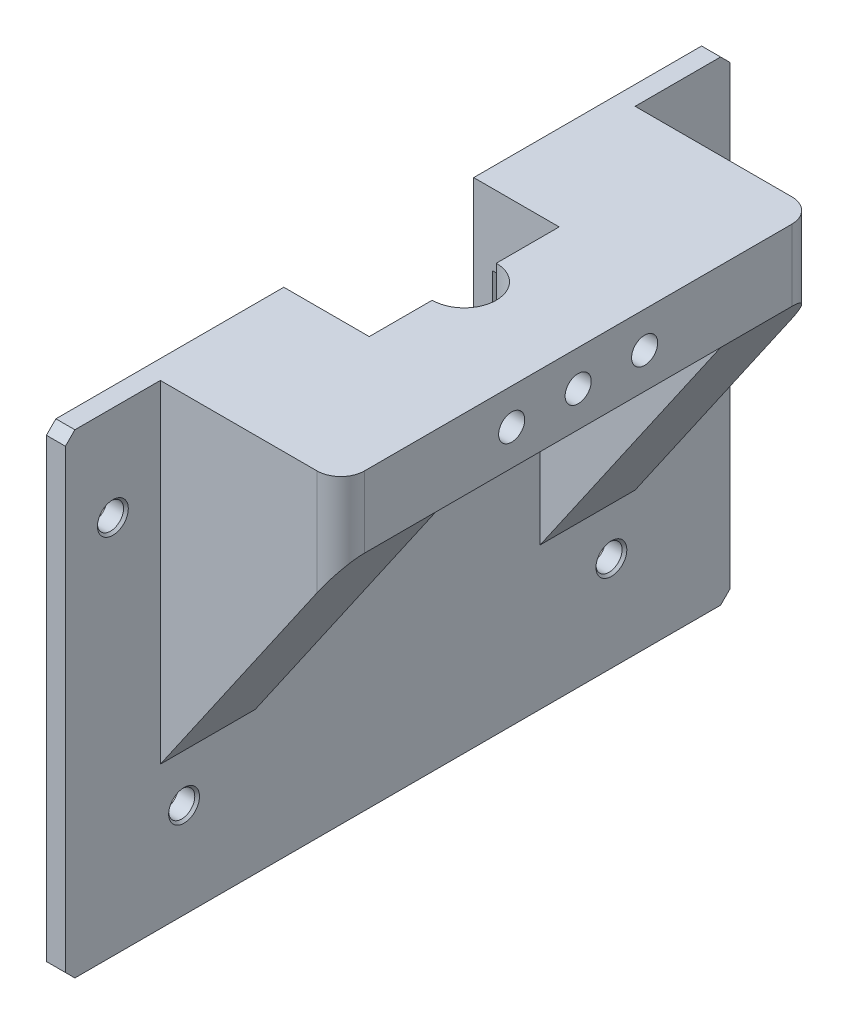
SolidWorks part; units mm, degrees
ref_plane "前视基准面" through (0, 0, 0) normal (0, 0, 1) x (1, 0, 0)
ref_plane "上视基准面" through (0, 0, 0) normal (0, 1, 0) x (1, 0, 0)
ref_plane "右视基准面" through (0, 0, 0) normal (1, 0, 0) x (0, 0, -1)
sketch "草图1" plane through (0, 0, 0) normal (1, 0, 0) x (0, 0, -1)
  line L1 (-70, 40) -> (70, 40)
  line L2 (-70, 40) -> (-70, -60)
  line L3 (-70, -60) -> (70, -60)
  line L4 (70, 40) -> (70, -60)
  dimension "D1" = 100
  dimension "D2" = 140
  dimension "D3" = 70
  dimension "D4" = 40
extrude "凸台-拉伸1" add sketch "草图1" along normal blind 4
sketch "草图9" plane through (4, 0, 0) normal (1, 0, 0) x (0, 0, -1)
  line L0 (70, -60) -> (70, 40) construction
  line L1 (-60, 20) -> (60, 20) construction
  line L2 (-60, 20) -> (-60, -40) construction
  line L3 (-60, -40) -> (60, -40) construction
  line L4 (60, 20) -> (60, -40) construction
  line L5 (70, 40) -> (-70, 40) construction
  circle A0 centre (-60, 20) radius 2.75
  circle A2 centre (60, 20) radius 2.75
  circle A4 centre (-45, -40) radius 2.75
  circle A5 centre (45, -40) radius 2.75
  dimension "D5" = 5.5
  dimension "D6" = 5.5
  dimension "D7" = 45
  dimension "D1" = 60
  dimension "D2" = 120
  dimension "D3" = 10
  dimension "D4" = 20
  dimension "D8" = 45
extrude "切除-拉伸3" cut sketch "草图9" against normal blind 8
chamfer "倒角2" distance 2 angle 45 4 edges at (2, -60, -70) (2, 40, -70) (2, 40, 70) (2, -60, 70)
sketch "草图11" plane through (4, 0, 0) normal (1, 0, 0) x (0, 0, -1)
  line L0 (68, 40) -> (-68, 40) construction
  line L1 (-20, 40) -> (20, 40)
  line L2 (-20, 40) -> (-20, -10)
  line L3 (-20, -10) -> (20, -10)
  line L4 (20, 40) -> (20, -10)
  dimension "D1" = 20
  dimension "D2" = 20
  dimension "D3" = 10
extrude "切除-拉伸5" cut sketch "草图11" against normal blind 5
sketch "草图12" plane through (4, 0, 0) normal (1, 0, 0) x (0, 0, -1)
  line L1 (-20, 40) -> (-30, 40)
  line L2 (-20, 40) -> (-20, 25)
  line L3 (-20, 25) -> (-30, 25)
  line L4 (-30, 40) -> (-30, 25)
  line L5 (20, 40) -> (30, 40)
  line L6 (20, 40) -> (20, 25)
  line L7 (20, 25) -> (30, 25)
  line L8 (30, 40) -> (30, 25)
  dimension "D1" = 10
  dimension "D2" = 10
  dimension "D3" = 15
  dimension "D4" = 15
extrude "凸台-拉伸2" add sketch "草图12" along normal blind 14
sketch "草图13" plane through (18, 0, 0) normal (1, 0, 0) x (0, 0, -1)
  line L1 (-30, 40) -> (30, 40)
  line L2 (-30, 40) -> (-30, 25)
  line L3 (-30, 25) -> (30, 25)
  line L4 (30, 40) -> (30, 25)
extrude "凸台-拉伸3" add sketch "草图13" along normal blind 14
sketch "草图14" plane through (0, 0, 30) normal (0, 0, 1) x (1, 0, 0)
  line L0 (4, 40) -> (4, -30)
  line L1 (4, 38) -> (4, -58) construction
  line L2 (4, -30) -> (32, 25)
  line L3 (32, 25) -> (32, 40)
  line L4 (32, 40) -> (4, 40)
  dimension "D1" = 55
extrude "凸台-拉伸4" add sketch "草图14" along normal blind 20
sketch "草图15" plane through (0, 0, -30) normal (0, 0, -1) x (-1, 0, 0)
  line L4 (-4, 40) -> (-32, 40)
  line L5 (-4, -30) -> (-4, 40)
  line L6 (-32, 25) -> (-4, -30)
  line L7 (-32, 40) -> (-32, 25)
  line L8 (-4, 40) -> (-32, 40)
  line L9 (-4, -30) -> (-4, 40)
  line L10 (-32, 25) -> (-4, -30)
  line L11 (-32, 40) -> (-32, 25)
  dimension "D1" = 0
extrude "凸台-拉伸5" add sketch "草图15" along normal blind 20
sketch "草图16" plane through (0, 40, 0) normal (0, 1, 0) x (1, 0, 0)
  line L0 (18, 20) -> (18, -20) construction
  circle A0 centre (18, 0) radius 6.75
  dimension "D1" = 13.5
extrude "切除-拉伸6" cut sketch "草图16" against normal blind 20
sketch "草图17" plane through (32, 0, 0) normal (1, 0, 0) x (0, 0, -1)
  line L6 (50, 40) -> (-50, 40)
  line L7 (-50, 40) -> (-50, 25)
  line L8 (-50, 25) -> (-30, 25)
  line L9 (-30, 25) -> (30, 25)
  line L10 (30, 25) -> (50, 25)
  line L11 (50, 25) -> (50, 40)
  line L12 (50, 40) -> (-50, 40)
  line L13 (-50, 40) -> (-50, 25)
  line L14 (-50, 25) -> (-30, 25)
  line L15 (-30, 25) -> (30, 25)
  line L16 (30, 25) -> (50, 25)
  line L17 (50, 25) -> (50, 40)
  dimension "D1" = 0
extrude "凸台-拉伸6" add sketch "草图17" along normal blind 10
sketch "草图18" plane through (18, 0, 0) normal (-1, 0, 0) x (0, 0, 1)
  line L0 (6.75, 40) -> (20, 40) construction
  line L1 (-20, 40) -> (-6.75, 40) construction
  circle A0 centre (14, 32.5) radius 2.75
  circle A1 centre (-14, 32.5) radius 2.75
  dimension "D1" = 5.5
  dimension "D2" = 5.5
  dimension "D3" = 28
  dimension "D4" = 14
  dimension "D5" = 7.5
  dimension "D6" = 7.5
extrude "切除-拉伸7" cut sketch "草图18" against normal through all
sketch "草图19" plane through (42, 0, 0) normal (1, 0, 0) x (0, 0, -1)
  circle A0 centre (0, 32.5) radius 2.75
  dimension "D1" = 5.5
  dimension "D2" = 32.5
extrude "切除-拉伸8" cut sketch "草图19" against normal blind 100
chamfer "倒角3" distance 0.5 angle 45 4 edges at (4, -40, 42.25) (4, -40, -47.75) (4, 20, -62.75) (4, 20, 57.25)
sketch "草图20" plane through (0, 0, 50) normal (0, 0, 1) x (1, 0, 0)
  line L0 (42, 25) -> (4, -30)
  line L1 (4, -30) -> (32, 25)
  line L2 (32, 25) -> (42, 25)
extrude "凸台-拉伸7" add sketch "草图20" against normal blind 20
sketch "草图21" plane through (0, 0, -50) normal (0, 0, -1) x (-1, 0, 0)
  line L0 (-42, 25) -> (-4, -30)
  line L1 (-4, -30) -> (-32, 25)
  line L2 (-32, 25) -> (-42, 25)
extrude "凸台-拉伸8" add sketch "草图21" against normal blind 20
fillet "圆角1" radius 5 2 edges at (42, 32.5, -50) (42, 32.5, 50)
